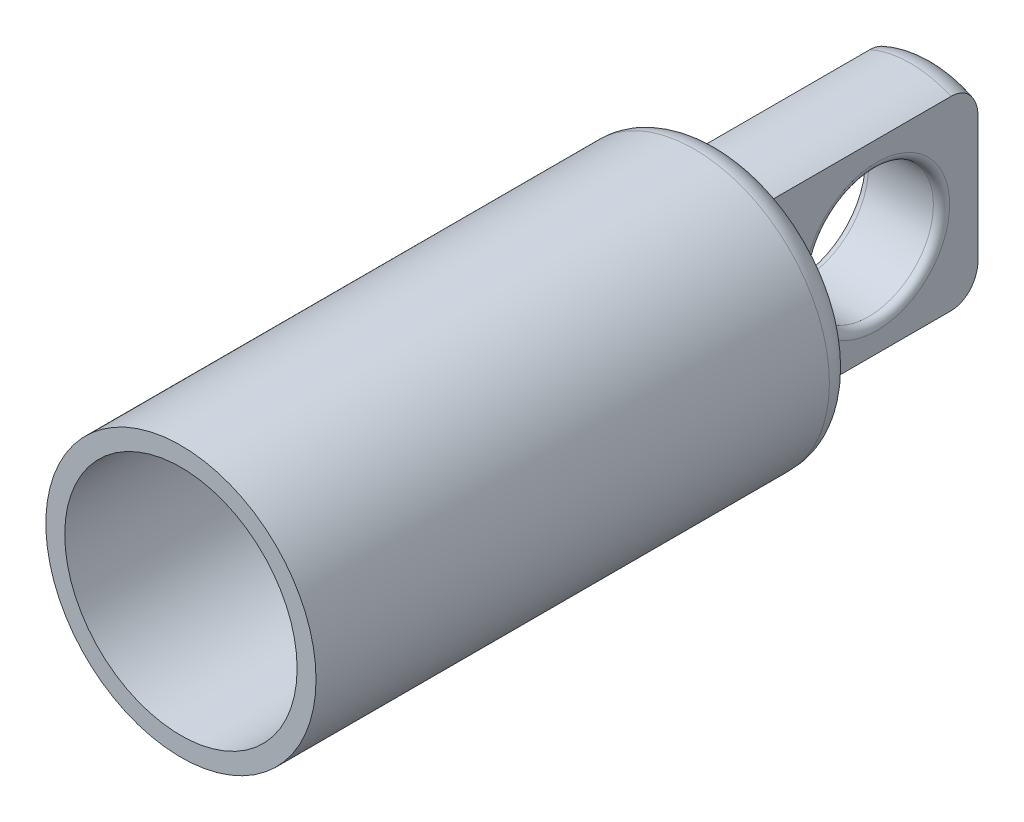
SolidWorks part; units mm, degrees
material "6061-T6 (SS)"
ref_plane "Front Plane" through (0, 0, 0) normal (0, 0, 1) x (1, 0, 0)
ref_plane "Top Plane" through (0, 0, 0) normal (0, 1, 0) x (1, 0, 0)
ref_plane "Right Plane" through (0, 0, 0) normal (1, 0, 0) x (0, 0, -1)
sketch "Sketch1" plane through (0, 0, 0) normal (0, 0, 1) x (1, 0, 0)
  circle A0 centre (0, 0) radius 6.35
  dimension "D1" = 12.7
extrude "Boss-Extrude1" add sketch "Sketch1" along normal blind 25.4
cosmetic thread "Cosmetic Thread1" parameters "D1"=19.05, "D2"=12.7
shell "Shell1" thickness 0.889
cosmetic thread "Cosmetic Thread2" parameters "D1"=9.525, "D2"=12.7
fillet "Fillet1" radius 1.27 1 edges at (6.35, 0, 0)
sketch "Sketch2" plane through (0, 0, 0) normal (0, 0, -1) x (-1, 0, 0)
  circle A0 centre (0, 0) radius 4.7625
  dimension "D1" = 9.525
extrude "Boss-Extrude2" add sketch "Sketch2" along normal blind 10.16
sketch "Sketch3" plane through (0, 0, -10.16) normal (0, 0, -1) x (-1, 0, 0)
  line L0 (0, -1000) -> (0, 49000) construction
  line L1 (-1.905, 4.3649) -> (-1.905, -4.3649)
  line L2 (1.905, 4.3649) -> (1.905, -4.3649)
  circle A0 centre (0, 0) radius 4.7625 construction
  circle A1 centre (0, 0) radius 4.7625 construction
  arc A2 (-1.905, 4.3649) -> (-1.905, -4.3649) centre (0, 0) ccw
  arc A3 (1.905, 4.3649) -> (1.905, -4.3649) centre (0, 0) cw
  dimension "D1" = 3.81
  dimension "D2" = 1.905
extrude "Cut-Extrude1" cut sketch "Sketch3" against normal up to surface (10.16 mm away) up to face at (4.7625, 0, 0)
sketch "Sketch4" plane through (1.905, 0, 0) normal (1, 0, 0) x (0, 0, -1)
  line L0 (10.16, -4.3649) -> (10.16, 4.3649) construction
  circle A0 centre (5.3975, 0) radius 3.048
  dimension "D1" = 6.096
  dimension "D2" = 4.7625
extrude "Cut-Extrude2" cut sketch "Sketch4" against normal through all
fillet "Fillet2" radius 0.381 2 edges at (-1.905, 0, -8.4455) (1.905, 0, -8.4455)
fillet "Fillet3" radius 1.27 2 edges at (0, -4.7625, -10.16) (0, 4.7625, -10.16)
